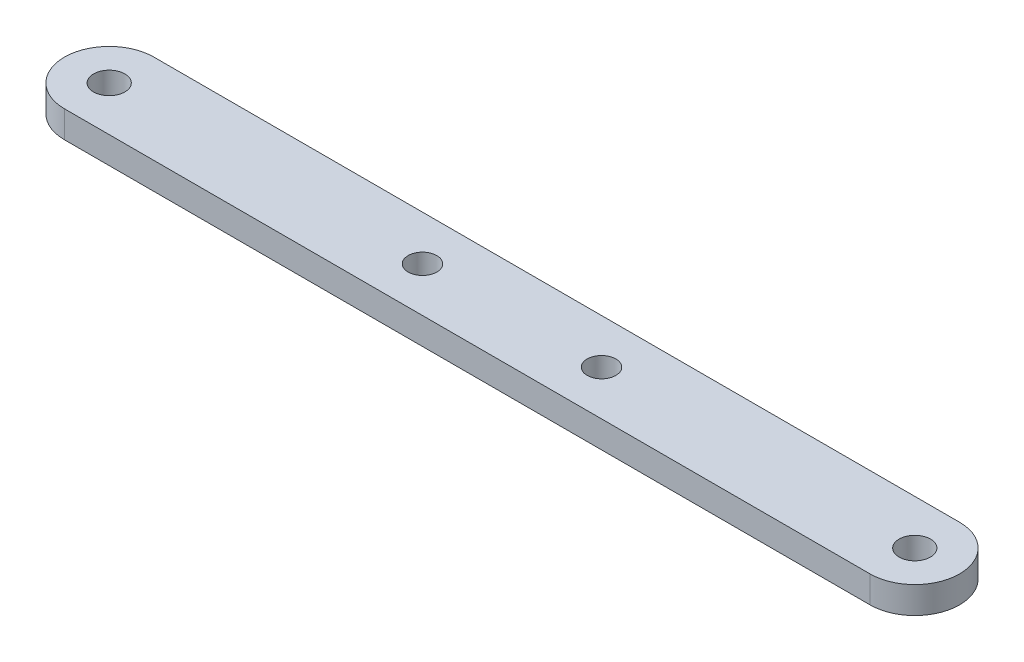
SolidWorks part; units mm, degrees
ref_plane "Front Plane" through (0, 0, 0) normal (0, 0, 1) x (1, 0, 0)
ref_plane "Top Plane" through (0, 0, 0) normal (0, 1, 0) x (1, 0, 0)
ref_plane "Right Plane" through (0, 0, 0) normal (1, 0, 0) x (0, 0, -1)
sketch "Sketch1" plane through (0, 0, 0) normal (0, 1, 0) x (1, 0, 0)
  line L1 (-45, 0) -> (45, 0) construction
  line L4 (-45, 0) -> (45, 0) construction
  line L5 (-45, 5) -> (45, 5)
  line L8 (-45, -5) -> (45, -5)
  line L11 (0, 0) -> (0, 13.1153) construction
  arc A12 (-45, 5) -> (-45, -5) centre (-45, 0) ccw
  arc A13 (45, -5) -> (45, 5) centre (45, 0) ccw
  circle A14 centre (-45, 0) radius 1.75
  circle A15 centre (45, 0) radius 1.75
  circle A16 centre (-10, 0) radius 1.6
  circle A17 centre (10, 0) radius 1.6
  point P0 (0, 0)
  point P4 (0, 0)
  dimension "D4" = 3.2
  dimension "D5" = 10
  dimension "D2" = 5
  dimension "D3" = 3.5
  dimension "D1" = 90
extrude "Boss-Extrude1" add sketch "Sketch1" along normal blind 3
